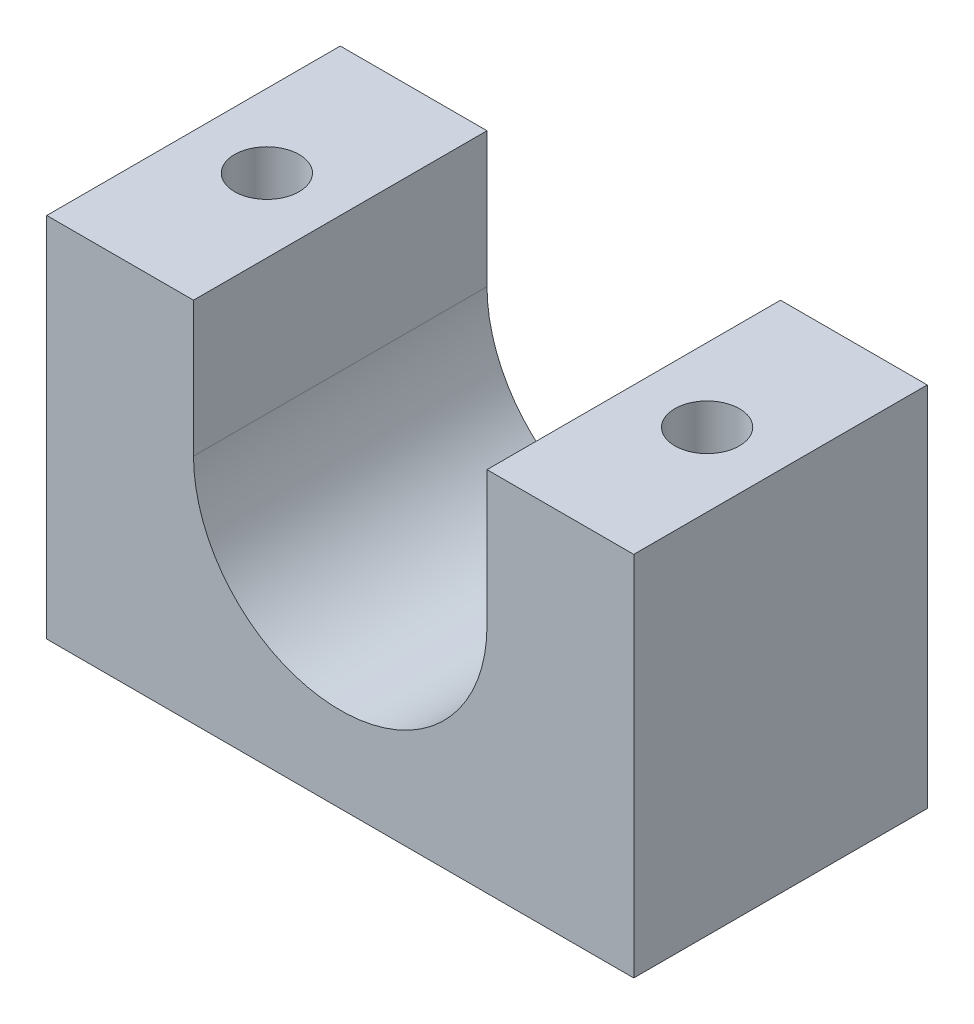
SolidWorks part; units mm, degrees
ref_plane "Front Plane" through (0, 0, 0) normal (0, 0, 1) x (1, 0, 0)
ref_plane "Top Plane" through (0, 0, 0) normal (0, 1, 0) x (1, 0, 0)
ref_plane "Right Plane" through (0, 0, 0) normal (1, 0, 0) x (0, 0, -1)
ref_plane "Plane1" through (0, 0, 20) normal (0, 0, 1) x (1, 0, 0)
sketch "Sketch1" plane through (0, 0, 20) normal (0, 0, 1) x (1, 0, 0)
  line L0 (20, -15.8) -> (20, 9.2)
  line L1 (20, 9.2) -> (-20, 9.2)
  line L2 (-20, 9.2) -> (-20, -15.8)
  line L3 (-20, -15.8) -> (20, -15.8)
extrude "Boss-Extrude1" add sketch "Sketch1" against normal blind 20
sketch "Sketch2" plane through (0, 0, 0) normal (0, 0, -1) x (-1, 0, 0)
  line L0 (10, 9.2) -> (-10, 9.2)
  line L1 (-10, 9.2) -> (-10, 0)
  line L2 (10, 0) -> (10, 9.2)
  arc A0 (-10, 0) -> (10, 0) centre (0, 0) ccw
extrude "Cut-Extrude1" cut sketch "Sketch2" against normal through all
hole_wizard "Hole1" positions "Sketch4" profile "Sketch3" legacy
sketch "Sketch4" plane through (0, 9.2, 0) normal (0, 1, 0) x (-1, 0, 0)
  point P0 (15, 10)
sketch "Sketch3" plane through (-15, 9.2, 10) normal (1, 0, 0) x (0, 0, 1)
  line L0 (0, 0) -> (0, 25)
  line L1 (0, 25) -> (2.2, 25)
  line L2 (2.2, 25) -> (2.2, 0)
  line L3 (2.2, 0) -> (0, 0)
  line L4 (0, 110) -> (0, -10) construction
  dimension "Diameter" = 4.4
  dimension "Depth" = 25
hole_wizard "Hole2" positions "Sketch6" profile "Sketch5" legacy
sketch "Sketch6" plane through (0, 9.2, 0) normal (0, 1, 0) x (-1, 0, 0)
  point P0 (-15, 10)
sketch "Sketch5" plane through (15, 9.2, 10) normal (1, 0, 0) x (0, 0, 1)
  line L0 (0, 0) -> (0, 25)
  line L1 (0, 25) -> (2.2, 25)
  line L2 (2.2, 25) -> (2.2, 0)
  line L3 (2.2, 0) -> (0, 0)
  line L4 (0, 110) -> (0, -10) construction
  dimension "Diameter" = 4.4
  dimension "Depth" = 25
